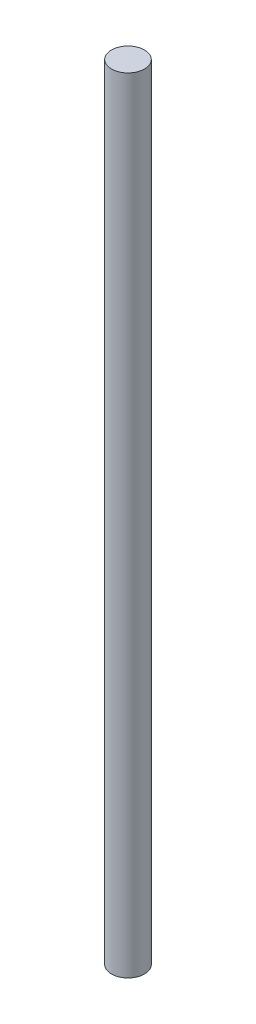
SolidWorks part; units mm, degrees
ref_plane "Front Plane" through (0, 0, 0) normal (0, 0, 1) x (1, 0, 0)
ref_plane "Top Plane" through (0, 0, 0) normal (0, 1, 0) x (1, 0, 0)
ref_plane "Right Plane" through (0, 0, 0) normal (1, 0, 0) x (0, 0, -1)
sketch "Sketch1" plane through (0, 0, 0) normal (0, 1, 0) x (1, 0, 0)
  circle A0 centre (0, 0) radius 2
  dimension "D1" = 4
extrude "Boss-Extrude1" add sketch "Sketch1" along normal blind 95
